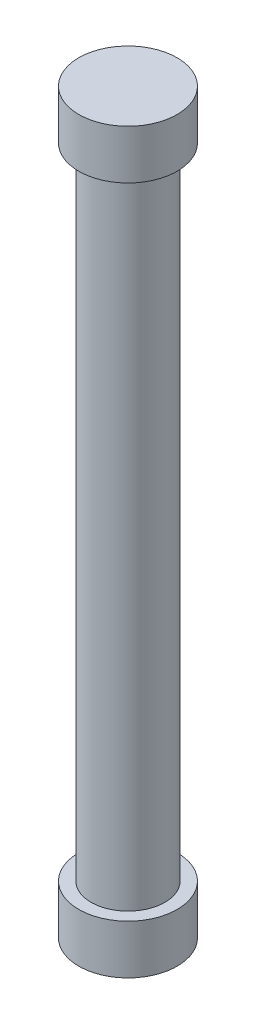
SolidWorks part; units mm, degrees
ref_plane "Front Plane" through (0, 0, 0) normal (0, 0, 1) x (1, 0, 0)
ref_plane "Top Plane" through (0, 0, 0) normal (0, 1, 0) x (1, 0, 0)
ref_plane "Right Plane" through (0, 0, 0) normal (1, 0, 0) x (0, 0, -1)
sketch "Sketch1" plane through (0, 0, 0) normal (0, 0, 1) x (1, 0, 0)
  line L0 (0, 19.89) -> (0, -10.11)
  line L1 (0, -10.11) -> (-2, -10.11)
  line L2 (-2, -10.11) -> (-2, -8.11)
  line L3 (-2, -8.11) -> (-1.5, -8.11)
  line L4 (-1.5, -8.11) -> (-1.5, 17.89)
  line L5 (-1.5, 17.89) -> (-2, 17.89)
  line L6 (-2, 17.89) -> (-2, 19.89)
  line L7 (-2, 19.89) -> (0, 19.89)
  dimension "D1" = 1.5
  dimension "D2" = 2
  dimension "D3" = 2
  dimension "D4" = 30
  dimension "D5" = 2
  dimension "D6" = 2
revolve "Revolve1" add sketch "Sketch1" angle 360 about L0
